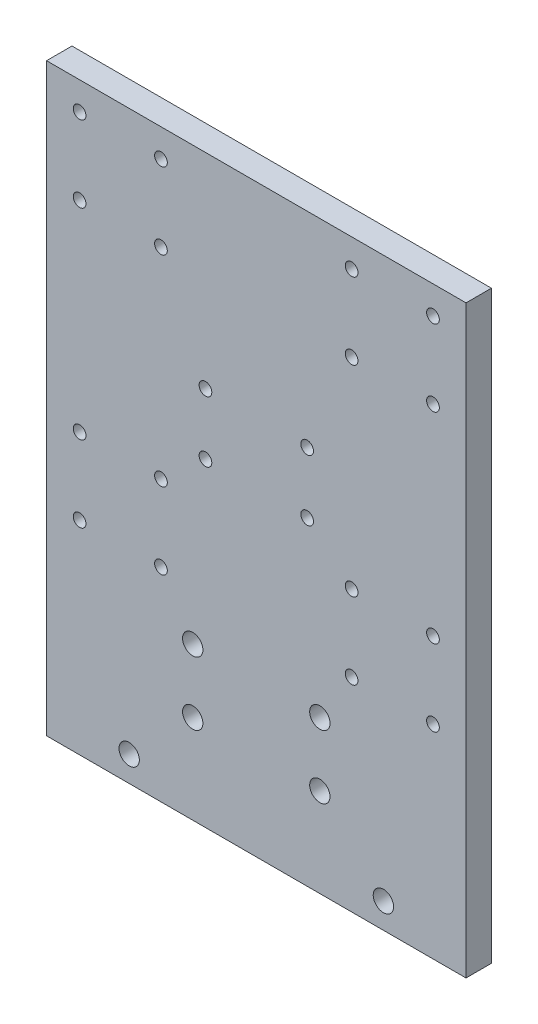
SolidWorks part; units mm, degrees
ref_plane "Front Plane" through (0, 0, 0) normal (0, 0, 1) x (1, 0, 0)
ref_plane "Top Plane" through (0, 0, 0) normal (0, 1, 0) x (1, 0, 0)
ref_plane "Right Plane" through (0, 0, 0) normal (1, 0, 0) x (0, 0, -1)
sketch "Sketch1" plane through (0, 0, 0) normal (0, 0, 1) x (1, 0, 0)
  line L1 (-82.5, 115) -> (82.5, 115)
  line L2 (-82.5, 115) -> (-82.5, -115)
  line L3 (-82.5, -115) -> (82.5, -115)
  line L4 (82.5, 115) -> (82.5, -115)
  line L5 (-82.5, 115) -> (82.5, -115) construction
  line L6 (-82.5, -115) -> (82.5, 115) construction
  point P0 (0, 0)
  dimension "D1" = 230
  dimension "D2" = 165
extrude "Boss-Extrude1" add sketch "Sketch1" along normal blind 10
hole_wizard "Otwór Ø5.0 (5)1" positions "Szkic2" profile "Szkic1" hole size "Ø5.0" standard "ISO" end condition through all
sketch "Szkic2" plane through (0, 0, 0) normal (0, 0, -1) x (-1, 0, 0)
  line L0 (82.5, -115) -> (-82.5, -115) construction
  line L1 (-82.5, -115) -> (-82.5, 115) construction
  point P0 (-69.5, 104)
  point P2 (-37.5, 104)
  point P4 (-37.5, 74)
  point P6 (-69.5, 74)
  point P8 (-69.5, -5)
  point P10 (-37.5, -5)
  point P12 (-37.5, -35)
  point P14 (-69.5, -35)
  point P16 (37.5, 104)
  point P18 (69.5, 104)
  point P20 (69.5, 74)
  point P22 (37.5, 74)
  point P24 (37.5, -5)
  point P26 (69.5, -5)
  point P28 (69.5, -35)
  point P30 (37.5, -35)
  point P32 (-20, 34.5)
  point P34 (20, 34.5)
  point P36 (20, 10.5)
  point P38 (-20, 10.5)
  dimension "D1" = 80
  dimension "D2" = 110
  dimension "D3" = 80
  dimension "D4" = 110
  dimension "D5" = 13
  dimension "D6" = 13
  dimension "D7" = 13
  dimension "D8" = 13
  dimension "D9" = 45
  dimension "D10" = 45
  dimension "D11" = 45
  dimension "D12" = 45
  dimension "D13" = 125.5
  dimension "D14" = 149.5
  dimension "D15" = 125.5
  dimension "D16" = 149.5
  dimension "D17" = 80
  dimension "D18" = 80
  dimension "D19" = 110
  dimension "D20" = 110
  dimension "D21" = 189
  dimension "D22" = 189
  dimension "D23" = 219
  dimension "D24" = 219
  dimension "D25" = 189
  dimension "D26" = 189
  dimension "D27" = 219
  dimension "D28" = 219
  dimension "D29" = 62.5
  dimension "D30" = 62.5
  dimension "D31" = 102.5
  dimension "D32" = 102.5
  dimension "D33" = 120
  dimension "D34" = 120
  dimension "D35" = 152
  dimension "D36" = 152
  dimension "D37" = 120
  dimension "D38" = 120
  dimension "D39" = 152
  dimension "D40" = 152
sketch "Szkic1" plane through (69.5, 104, 0) normal (1, 0, 0) x (0, 1, 0)
  line L0 (0, 0) -> (0, 10)
  line L1 (0, 10) -> (2.5, 10)
  line L2 (2.5, 10) -> (2.5, 0)
  line L5 (2.5, 0) -> (0, 0)
  line L11 (0, -6.35) -> (0, 107.95) construction
  dimension "Średnica otworu na wylot" = 5
  dimension "Głębokość otworu na wylot" = 10
hole_wizard "Otwór Ø8.0 (8)1" positions "Szkic4" profile "Szkic3" hole size "Ø8.0" standard "ISO" end condition through all
sketch "Szkic4" plane through (0, 0, 10) normal (0, 0, 1) x (1, 0, 0)
  line L1 (-82.5, 115) -> (-82.5, -115) construction
  line L3 (-82.5, -115) -> (82.5, -115) construction
  point P0 (-25, -55)
  point P2 (25, -55)
  point P4 (25, -80)
  point P6 (-25, -80)
  dimension "D1" = 50
  dimension "D2" = 50
  dimension "D3" = 25
  dimension "D4" = 25
  dimension "D5" = 57.5
  dimension "D6" = 35
  dimension "D7" = 35
sketch "Szkic3" plane through (-25, -55, 10) normal (1, 0, 0) x (0, -1, 0)
  line L0 (0, 0) -> (0, 10)
  line L1 (0, 10) -> (4, 10)
  line L2 (4, 10) -> (4, 0)
  line L5 (4, 0) -> (0, 0)
  line L11 (0, -6.35) -> (0, 107.95) construction
  dimension "Średnica otworu na wylot" = 8
  dimension "Głębokość otworu na wylot" = 10
hole_wizard "Otwór Ø8.0 (8)2" positions "Szkic6" profile "Szkic5" hole size "Ø8.0" standard "ISO" end condition through all
sketch "Szkic6" plane through (0, 0, 10) normal (0, 0, 1) x (1, 0, 0)
  line L0 (-82.5, 115) -> (-82.5, -115) construction
  line L1 (82.5, -115) -> (82.5, 115) construction
  line L2 (-82.5, -115) -> (82.5, -115) construction
  point P0 (50, -105)
  point P2 (-50, -105)
  dimension "D1" = 32.5
  dimension "D2" = 32.5
  dimension "D3" = 10
  dimension "D4" = 10
sketch "Szkic5" plane through (50, -105, 10) normal (1, 0, 0) x (0, -1, 0)
  line L0 (0, 0) -> (0, 10)
  line L1 (0, 10) -> (4, 10)
  line L2 (4, 10) -> (4, 0)
  line L5 (4, 0) -> (0, 0)
  line L11 (0, -6.35) -> (0, 107.95) construction
  dimension "Średnica otworu na wylot" = 8
  dimension "Głębokość otworu na wylot" = 10
